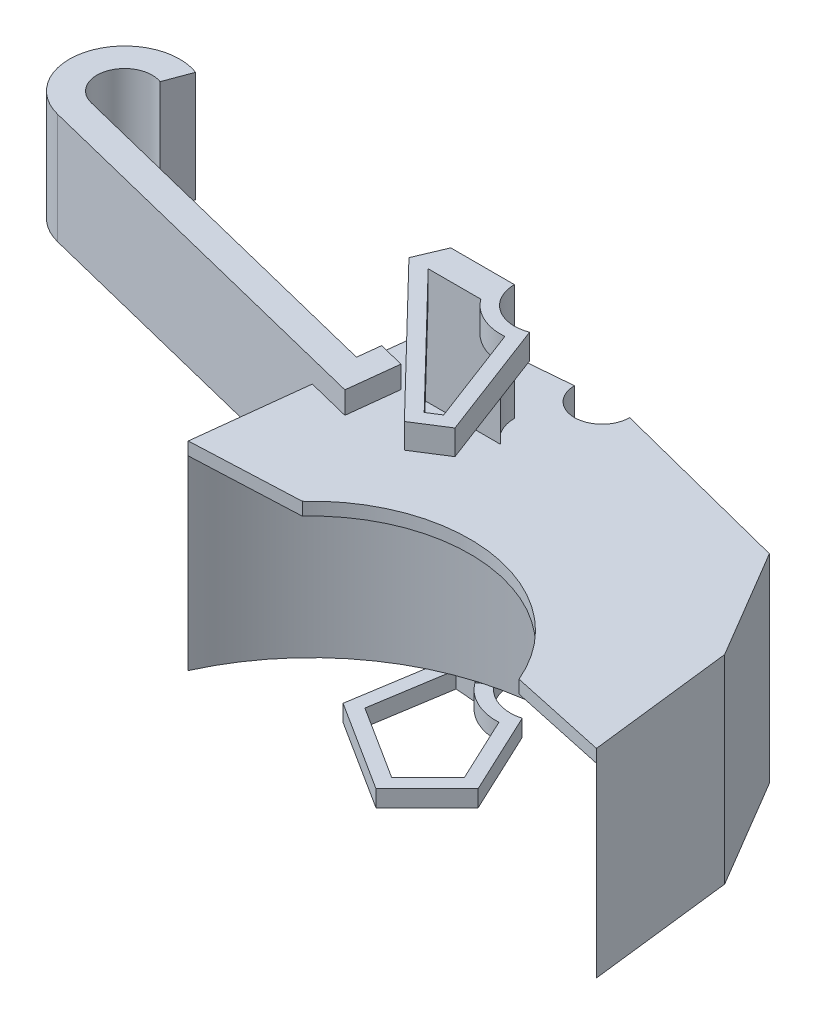
SolidWorks part; units mm, degrees
material "Custom Plastic"
ref_plane "X-Y Datum" through (0, 0, 0) normal (0, 0, 1) x (1, 0, 0)
ref_plane "X-Z Datum" through (0, 0, 0) normal (0, 1, 0) x (1, 0, 0)
ref_plane "Y-Z Datum" through (0, 0, 0) normal (1, 0, 0) x (0, 0, -1)
sketch "Sketch3" plane through (0, 0, 0) normal (0, 1, 0) x (1, 0, 0)
  line L3 (-475.1548, -2.1008) -> (-501.4647, -4.3447)
  line L5 (-333.5809, -74.5929) -> (-325.668, -141.4784)
  line L6 (-449.7548, -2.1008) -> (-363.4511, -24.1746)
  line L7 (-363.4511, -24.1746) -> (-333.5809, -74.5929)
  line L8 (-541.9592, -112.9069) -> (-530.9704, -16.9258)
  line L9 (-530.9704, -16.9258) -> (-501.4647, -4.3447)
  circle A0 centre (-438.15, -160.02) radius 114 construction
  arc A1 (-324.3062, -165.9863) -> (-551.9938, -154.0537) centre (-438.15, -160.02) ccw construction
  arc A2 (-325.668, -141.4784) -> (-541.9592, -112.9069) centre (-438.15, -160.02) ccw
  arc A3 (-475.1548, -2.1008) -> (-449.7548, -2.1008) centre (-462.4548, -2.1008) ccw
  arc A4 (-471.9814, -10.4992) -> (-451.2668, -8.1108) centre (-462.4548, -2.1008) ccw construction
extrude "Boss-Extrude1" add sketch "Sketch3" against normal blind 76.2 and the other way blind 15.24
sketch "Sketch4" plane through (0, 68.54, 0) normal (0, 1, 0) x (1, 0, 0)
  line L0 (-505.1995, -28.9416) -> (-510.9242, -42.4549)
  line L1 (-446.7271, -108.7426) -> (-510.9242, -42.4549) construction
  line L2 (-510.9242, -42.4549) -> (-446.7271, -108.7426)
  line L3 (-446.7271, -108.7426) -> (-432.5063, -99.7069)
  line L4 (-432.5063, -99.7069) -> (-453.4851, -44.4233)
  line L5 (-505.1995, -28.9416) -> (-475.9187, -28.9416) construction
  line L6 (-505.1995, -28.9416) -> (-475.9187, -28.9416)
  arc A1 (-453.4851, -44.4233) -> (-475.9187, -28.9416) centre (-459.36, -28.9417) cw
  arc A2 (-471.6257, -32.2343) -> (-458.0866, -41.5777) centre (-459.36, -28.9417) ccw construction
extrude "Boss-Extrude2" add sketch "Sketch4" against normal up to surface (11.43 mm away) separate body
shell "Shell3" thickness 6.35
sketch "Sketch11" plane through (0, 68.54, 0) normal (0, 1, 0) x (1, 0, 0)
  line L0 (-505.1995, -28.9416) -> (-510.9242, -42.4549)
  line L1 (-510.9242, -42.4549) -> (-468.93, -42.4549)
  line L2 (-505.1995, -28.9416) -> (-475.9187, -28.9416)
  line L6 (-505.1995, -28.9416) -> (-475.9187, -28.9416) construction
  line L8 (-505.1995, -28.9416) -> (-510.9242, -42.4549) construction
  line L9 (-510.9242, -42.4549) -> (-446.7271, -108.7426) construction
  arc A1 (-475.9187, -28.9416) -> (-453.4851, -44.4233) centre (-459.36, -28.9417) ccw construction
  arc A2 (-468.93, -42.4549) -> (-475.9187, -28.9416) centre (-459.36, -28.9417) cw
extrude "Boss-Extrude9" add sketch "Sketch11" against normal up to surface (53.3 mm away) up to face at (-438.9264, 15.24, 38.8918)
sketch "Sketch6" plane through (0, -92.1308, 0) normal (0, -1, 0) x (1, 0, 0)
  line L0 (-493.2979, 29.5925) -> (-501.6533, 82.0249)
  line L1 (-501.6533, 82.0249) -> (-460.0552, 108.4707)
  line L3 (-477.7843, 30.7504) -> (-493.2979, 29.5925)
  line L4 (-460.0552, 108.4707) -> (-436.5905, 84.9748)
  line L5 (-436.5905, 84.9748) -> (-454.4905, 46.8031)
  arc A0 (-477.7843, 30.7504) -> (-454.4905, 46.8031) centre (-459.3596, 28.9416) cw
  arc A1 (-461.5052, 41.4591) -> (-470.2931, 35.403) centre (-459.3596, 28.9416) ccw construction
extrude "Boss-Extrude4" add sketch "Sketch6" against normal up to surface (7.62 mm away) separate body
shell "Shell4" thickness 6.35
sketch "Sketch8" plane through (0, 15.24, 0) normal (0, 1, 0) x (1, 0, 0)
  line L9 (-371.0495, -131.7017) -> (-325.668, -141.4784)
  line L10 (-541.9592, -112.9069) -> (-491.7292, -110.6877)
  arc A0 (-325.668, -141.4784) -> (-541.9592, -112.9069) centre (-438.15, -160.02) ccw construction
  arc A1 (-325.668, -141.4784) -> (-541.9592, -112.9069) centre (-438.15, -160.02) ccw construction
  arc A2 (-491.7292, -110.6877) -> (-371.0495, -131.7017) centre (-438.15, -160.02) cw
  circle A3 centre (-438.15, -160.02) radius 6.75 construction
  arc A4 (-541.9592, -112.9069) -> (-325.668, -141.4784) centre (-438.15, -160.02) cw
  arc A5 (-325.668, -141.4784) -> (-541.9592, -112.9069) centre (-438.15, -160.02) ccw construction
sketch "Sketch9" plane through (0, 0, 0) normal (0, 1, 0) x (1, 0, 0)
  line L0 (-676.9388, 25.464) -> (-681.3694, 13.5619)
  line L1 (-526.4894, -51.0228) -> (-688.8633, -10.6652)
  line L2 (-516.1508, -66.6788) -> (-691.9267, -22.9902)
  line L7 (-516.1508, -66.6788) -> (-513.5028, -43.5501)
  line L8 (-513.5028, -43.5501) -> (-525.2983, -40.6184)
  line L9 (-525.2983, -40.6184) -> (-526.4894, -51.0228)
  line L10 (-530.9704, -16.9258) -> (-541.9592, -112.9069) construction
  circle A0 centre (-685.8, 1.6598) radius 12.7 construction
  arc A1 (-684.6727, -10.9901) -> (-673.3556, 4.1948) centre (-685.8, 1.6598) ccw construction
  arc A2 (-681.3694, 13.5619) -> (-688.8633, -10.6652) centre (-685.8, 1.6598) ccw
  arc A3 (-691.9267, -22.9902) -> (-676.9388, 25.464) centre (-685.8, 1.6598) cw
  dimension "D1" = 12.7
extrude "Boss-Extrude10" add sketch "Sketch8" against normal up to surface (5.9368 mm away)
extrude "Boss-Extrude11" add sketch "Sketch9" against normal blind 25.4 and the other way blind 25.4
sketch "Sketch12" plane through (0, -92.1308, 0) normal (0, -1, 0) x (1, 0, 0)
  line L0 (-493.2979, 29.5925) -> (-477.7843, 30.7504)
  line L1 (-493.2979, 29.5925) -> (-495.3217, 42.2925)
  line L2 (-501.6533, 82.0249) -> (-493.2979, 29.5925) construction
  line L3 (-495.3217, 42.2925) -> (-479.5361, 43.4707)
  line L4 (-479.5361, 43.4707) -> (-474.322, 39.8443)
  arc A0 (-454.4905, 46.8031) -> (-477.7843, 30.7504) centre (-459.3596, 28.9416) ccw construction
  arc A1 (-474.322, 39.8443) -> (-477.7843, 30.7504) centre (-459.3596, 28.9416) ccw
  arc A2 (-458.2326, 53.7794) -> (-482.9713, 36.7309) centre (-459.3596, 28.9416) ccw construction
  dimension "D1" = 12.7
extrude "Boss-Extrude12" add sketch "Sketch12" against normal up to surface (15.9308 mm away) up to face at (-438.9264, -76.2, 38.8918)
